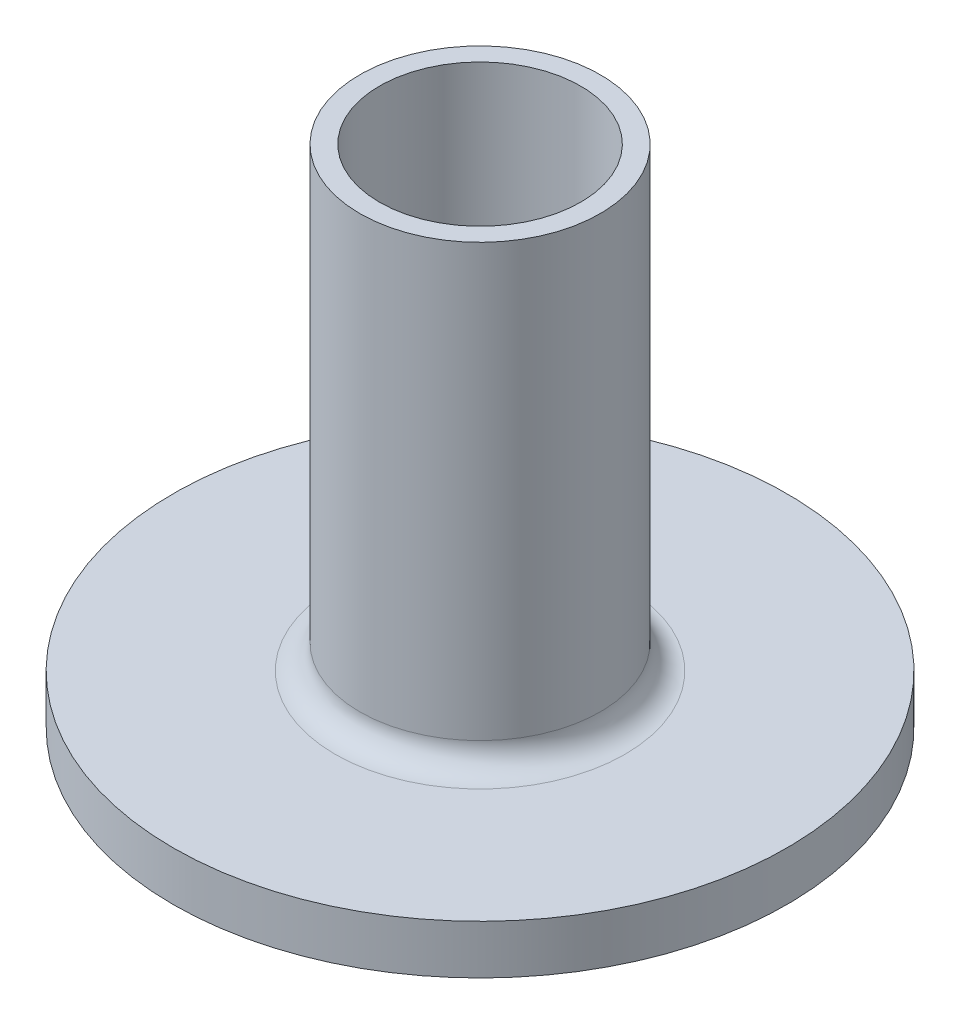
SolidWorks part; units mm, degrees
ref_plane "Alzado" through (0, 0, 0) normal (0, 0, 1) x (1, 0, 0)
ref_plane "Planta" through (0, 0, 0) normal (0, 1, 0) x (1, 0, 0)
ref_plane "Vista lateral" through (0, 0, 0) normal (1, 0, 0) x (0, 0, -1)
sketch "Croquis1" plane through (0, 0, 0) normal (0, 1, 0) x (1, 0, 0)
  circle A0 centre (0, 0) radius 6.25
  dimension "D1" = 12.5
extrude "Saliente-Extruir1" add sketch "Croquis1" along normal blind 1
sketch "Croquis2" plane through (0, 1, 0) normal (0, 1, 0) x (1, 0, 0)
  circle A0 centre (0, 0) radius 2.45
  dimension "D1" = 4.9
extrude "Saliente-Extruir2" add sketch "Croquis2" along normal blind 9.29
sketch "Croquis3" plane through (0, 10.29, 0) normal (0, 1, 0) x (1, 0, 0)
  circle A0 centre (0, 0) radius 2.05
  dimension "D1" = 4.1
extrude "Cortar-Extruir1" cut sketch "Croquis3" against normal through all
fillet "Redondeo1" radius 0.5 1 edges at (0, 1, 2.45)
